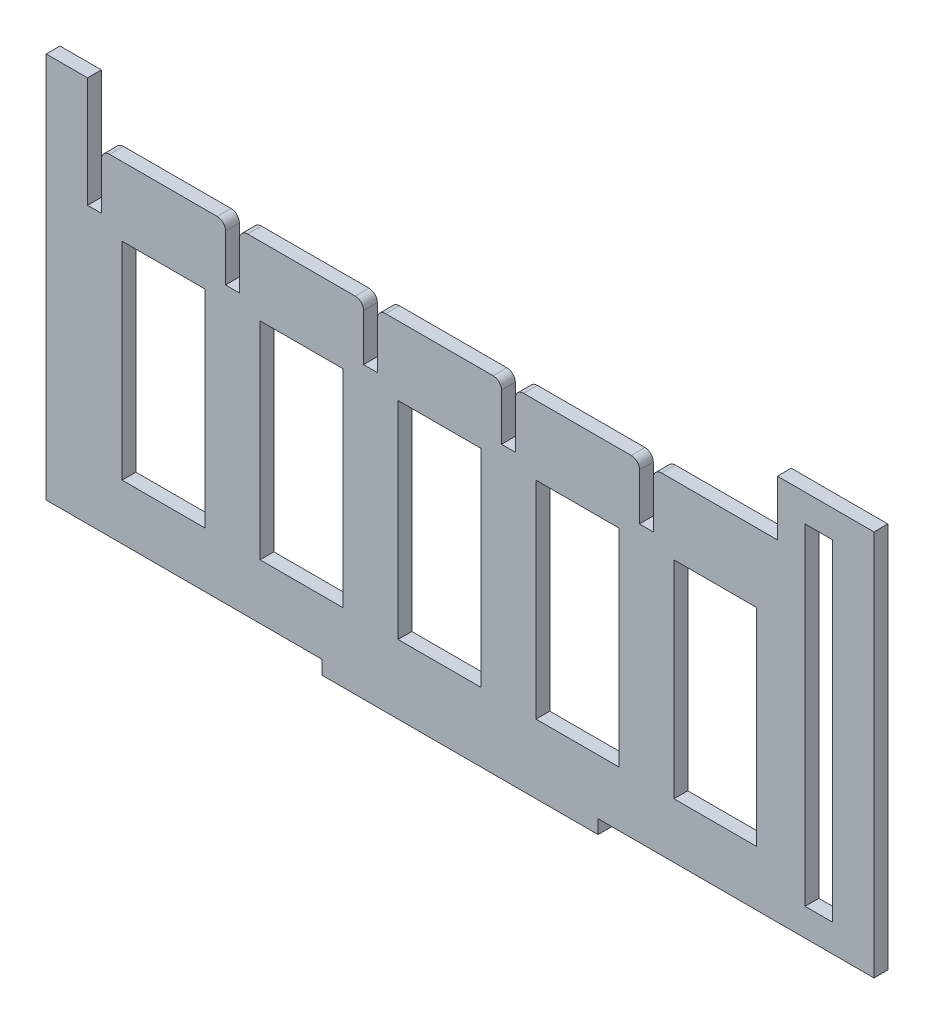
SolidWorks part; units mm, degrees
material "Perspex (TM) GS Acrylic Cast Sheet"
ref_plane "Ebene vorne" through (0, 0, 0) normal (0, 0, 1) x (1, 0, 0)
ref_plane "Ebene oben" through (0, 0, 0) normal (0, 1, 0) x (1, 0, 0)
ref_plane "Ebene rechts" through (0, 0, 0) normal (1, 0, 0) x (0, 0, -1)
sketch "Skizze1" plane through (0, 0, 0) normal (0, 0, 1) x (1, 0, 0)
  line L0 (0, 0) -> (0, -72.5) construction
  line L1 (-150, 70) -> (150, 70)
  line L2 (-150, 70) -> (-150, -70)
  line L3 (-150, -70) -> (150, -70)
  line L4 (150, 70) -> (150, -70)
  line L5 (-150, 70) -> (150, -70) construction
  line L6 (-150, -70) -> (150, 70) construction
  line L8 (50, -75) -> (-50, -75)
  line L9 (50, -75) -> (50, -70)
  line L10 (50, -70) -> (-50, -70)
  line L11 (-50, -75) -> (-50, -70)
  line L12 (50, -75) -> (-50, -70) construction
  line L13 (50, -70) -> (-50, -75) construction
  point P0 (0, 0)
  dimension "D1" = 300
  dimension "D2" = 140
  dimension "D3" = 5
  dimension "D4" = 100
extrude "Aufsatz-Linear austragen1" add sketch "Skizze1" along normal blind 5 contours L11 L8 L9 L3 | L4 L1 L2 L3
sketch "Skizze2" plane through (0, 0, 5) normal (0, 0, 1) x (1, 0, 0)
  line L2 (-135, 70) -> (115, 70)
  line L3 (-135, 70) -> (-135, 50)
  line L4 (-135, 50) -> (115, 50) construction
  line L5 (115, 70) -> (115, 50)
  line L6 (-135, 70) -> (115, 50) construction
  line L8 (-135, 50) -> (115, 70) construction
  line L10 (-130, 50) -> (-85, 50)
  line L11 (-80, 50) -> (-35, 50)
  line L12 (-135, 50) -> (-135, 30)
  line L13 (-135, 30) -> (-130, 30)
  line L14 (-130, 50) -> (-130, 30)
  line L15 (-135, 50) -> (-130, 30) construction
  line L16 (-135, 30) -> (-130, 50) construction
  line L17 (-30, 50) -> (15, 50)
  line L18 (-85, 50) -> (-85, 30)
  line L19 (-85, 30) -> (-80, 30)
  line L20 (-80, 50) -> (-80, 30)
  line L21 (-85, 50) -> (-80, 30) construction
  line L22 (-85, 30) -> (-80, 50) construction
  line L23 (20, 50) -> (65, 50)
  line L24 (-35, 50) -> (-35, 30)
  line L25 (-35, 30) -> (-30, 30)
  line L26 (-30, 50) -> (-30, 30)
  line L27 (-35, 50) -> (-30, 30) construction
  line L28 (-35, 30) -> (-30, 50) construction
  line L29 (70, 50) -> (115, 50)
  line L30 (15, 50) -> (15, 30)
  line L31 (15, 30) -> (20, 30)
  line L32 (20, 50) -> (20, 30)
  line L33 (15, 50) -> (20, 30) construction
  line L34 (15, 30) -> (20, 50) construction
  line L35 (-150, 70) -> (-150, -70) construction
  line L36 (65, 50) -> (65, 30)
  line L37 (65, 30) -> (70, 30)
  line L38 (70, 50) -> (70, 30)
  line L39 (65, 50) -> (70, 30) construction
  line L40 (65, 30) -> (70, 50) construction
  line L41 (-150, 70) -> (150, 70) construction
  point P4 (-10, 60)
  point P12 (-132.5, 40)
  point P17 (-82.5, 40)
  point P22 (-32.5, 40)
  point P27 (17.5, 40)
  point P32 (67.5, 40)
  dimension "D1" = 250
  dimension "D2" = 20
  dimension "D3" = 15
  dimension "D4" = 20
  dimension "D5" = 5
extrude "Schnitt-Linear austragen1" cut sketch "Skizze2" against normal through all
fillet "Verrundung1" radius 3 9 edges at (15, 50, 2.5) (65, 50, 2.5) (-35, 50, 2.5) (70, 50, 2.5) (20, 50, 2.5) (-30, 50, 2.5) (-80, 50, 2.5) (-85, 50, 2.5) (-130, 50, 2.5)
sketch "Skizze3" plane through (0, 0, 5) normal (0, 0, 1) x (1, 0, 0)
  line L5 (135, 60) -> (125, 60)
  line L6 (115, 70) -> (150, 70) construction
  line L7 (150, 70) -> (150, -70) construction
  line L8 (170, 25) -> (-150, 25) construction
  line L9 (-150, 70) -> (-150, -70) construction
  line L10 (-122.5, 25) -> (-92.5, 25)
  line L11 (-122.5, 25) -> (-122.5, -50)
  line L12 (-122.5, -50) -> (-92.5, -50)
  line L13 (-92.5, 25) -> (-92.5, -50)
  line L14 (-92.5, 25) -> (-72.5, 25) construction
  line L15 (-92.5, 25) -> (-92.5, -50) construction
  line L16 (-92.5, -50) -> (-72.5, -50) construction
  line L17 (-72.5, 25) -> (-72.5, -50) construction
  line L18 (-72.5, 25) -> (-42.5, 25)
  line L19 (-72.5, 25) -> (-72.5, -50)
  line L20 (-72.5, -50) -> (-42.5, -50)
  line L21 (-42.5, 25) -> (-42.5, -50)
  line L22 (-42.5, 25) -> (-22.5, 25) construction
  line L23 (-42.5, 25) -> (-42.5, -50) construction
  line L24 (-42.5, -50) -> (-22.5, -50) construction
  line L25 (-22.5, 25) -> (-22.5, -50) construction
  line L26 (-22.5, 25) -> (7.5, 25)
  line L27 (-22.5, 25) -> (-22.5, -50)
  line L28 (-22.5, -50) -> (7.5, -50)
  line L29 (7.5, 25) -> (7.5, -50)
  line L30 (7.5, 25) -> (27.5, 25)
  line L31 (7.5, 25) -> (7.5, -50)
  line L32 (7.5, -50) -> (27.5, -50)
  line L33 (27.5, 25) -> (27.5, -50)
  line L34 (27.5, 25) -> (57.5, 25)
  line L35 (27.5, 25) -> (27.5, -50)
  line L36 (27.5, -50) -> (57.5, -50)
  line L37 (57.5, 25) -> (57.5, -50)
  line L38 (57.5, 25) -> (77.5, 25) construction
  line L39 (57.5, 25) -> (57.5, -50) construction
  line L40 (57.5, -50) -> (77.5, -50) construction
  line L41 (77.5, 25) -> (77.5, -50) construction
  line L42 (77.5, 25) -> (107.5, 25)
  line L43 (77.5, 25) -> (77.5, -50)
  line L44 (77.5, -50) -> (107.5, -50)
  line L45 (107.5, 25) -> (107.5, -50)
  line L46 (135, 60) -> (135, -60)
  line L47 (135, -60) -> (125, -60)
  line L48 (125, 60) -> (125, -60)
  line L49 (-150, 70) -> (-135, 70) construction
  line L50 (-150, -70) -> (-50, -70) construction
  line L51 (50, -70) -> (150, -70) construction
  line L52 (115, 50) -> (115, 70) construction
  dimension "D1" = 10
  dimension "D2" = 30
  dimension "D3" = 20
  dimension "D4" = 45
  dimension "D5" = 20
  dimension "D6" = 15
  dimension "D7" = 27.5
  dimension "D8" = 10
  dimension "D9" = 10
extrude "Schnitt-Linear austragen2" cut sketch "Skizze3" against normal through all
